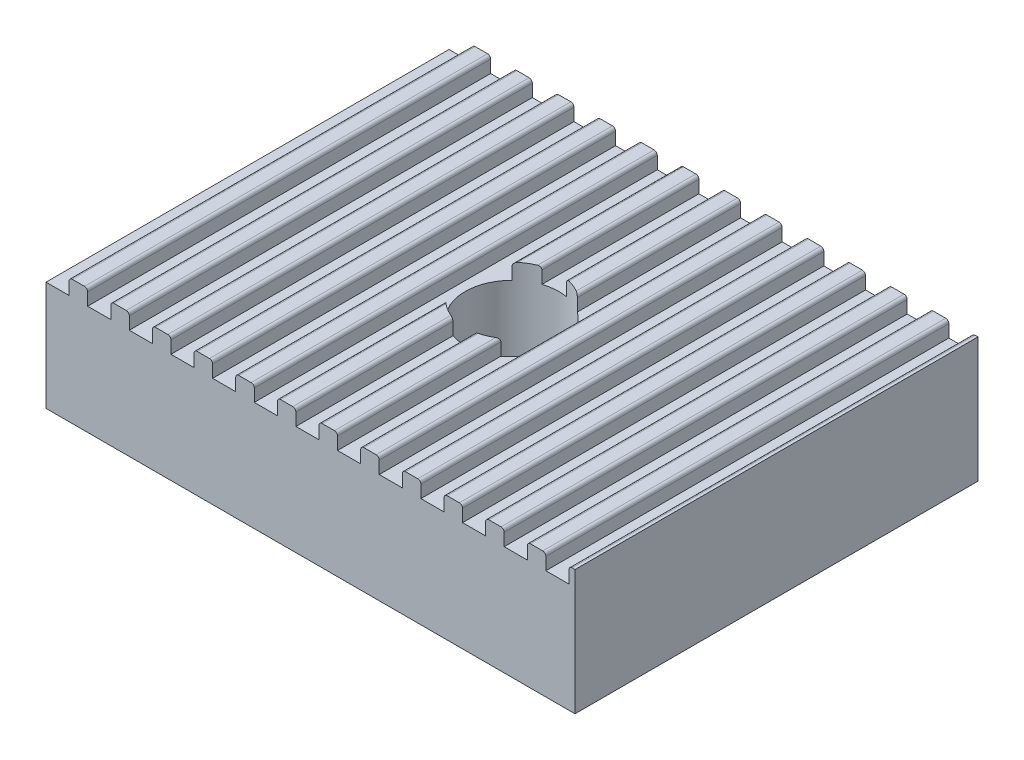
SolidWorks part; units mm, degrees
ref_plane "Front Plane" through (0, 0, 0) normal (0, 0, 1) x (1, 0, 0)
ref_plane "Top Plane" through (0, 0, 0) normal (0, 1, 0) x (1, 0, 0)
ref_plane "Right Plane" through (0, 0, 0) normal (1, 0, 0) x (0, 0, -1)
sketch "Sketch1" plane through (0, 0, 0) normal (0, 1, 0) x (1, 0, 0)
  line L1 (-12.7, -9.675) -> (12.7, -9.675)
  line L2 (-12.7, -9.675) -> (-12.7, 9.675)
  line L3 (-12.7, 9.675) -> (12.7, 9.675)
  line L4 (12.7, -9.675) -> (12.7, 9.675)
  line L5 (-12.7, -9.675) -> (12.7, 9.675) construction
  line L6 (-12.7, 9.675) -> (12.7, -9.675) construction
  point P0 (0, 0)
  dimension "D1" = 25.4
  dimension "D2" = 19.35
extrude "Boss-Extrude1" add sketch "Sketch1" along normal blind 6
sketch "Sketch2" plane through (0, 0, 9.675) normal (0, 0, 1) x (1, 0, 0)
  line L0 (-12.7, 5.25) -> (-11.59, 5.25)
  line L1 (-12.7, 6) -> (-12.7, 0) construction
  line L2 (-11.59, 5.25) -> (-11.59, 6)
  line L3 (-12.7, 6) -> (12.7, 6) construction
  line L4 (-11.59, 6) -> (-10.7, 6)
  line L5 (-9.59, 6) -> (-9.59, 5.25)
  line L6 (-9.59, 5.25) -> (-10.7, 5.25)
  line L7 (-10.7, 5.25) -> (-10.7, 6)
  line L8 (-12.7, 5.25) -> (-12.7, 6)
  line L9 (-9.59, 6) -> (-10.7, 6)
  line L10 (-11.59, 6) -> (-12.7, 6)
  line M3 (12.7, 6) -> (-12.7, 6)
  line M4 (-12.7, 6) -> (-12.7, 0)
  dimension "D1" = 0.75
  dimension "D2" = 1.11
  dimension "D3" = 0.89
extrude "Cut-Extrude3" cut sketch "Sketch2" against normal through all contours L0 L2 M3 M4
pattern_linear "LPattern2" count 13 spacing 2 along (1, 0, 0) of "Cut-Extrude3"
fillet "Fillet1" radius 0.15 25 edges at (-10.7, 6, 0) (-11.59, 6, 0) (12.41, 6, 0) (10.41, 6, 0) (11.3, 6, 0) (8.41, 6, 0) (9.3, 6, 0) (6.41, 6, 0) (7.3, 6, 0) (4.41, 6, 0) (5.3, 6, 0) (2.41, 6, 0) (3.3, 6, 0) (0.41, 6, 0) (1.3, 6, 0) (-1.59, 6, 0) (-0.7, 6, 0) (-3.59, 6, 0) (-2.7, 6, 0) (-5.59, 6, 0) (-4.7, 6, 0) (-7.59, 6, 0) (-6.7, 6, 0) (-9.59, 6, 0) (-8.7, 6, 0)
sketch "Sketch3" plane through (0, 0, 0) normal (0, -1, 0) x (1, 0, 0)
  point P0 (0, 0)
hole_wizard "M4 Clearance Hole1" positions "Sketch4" profile "Sketch5" hole size "M4" standard "ANSI Metric" end condition through all
sketch "Sketch4" plane through (0, 0, 0) normal (0, -1, 0) x (-1, 0, 0)
  point P0 (0, 0)
sketch "Sketch5" plane through (0, 0, 0) normal (1, 0, 0) x (0, 0, -1)
  line L0 (0, 0) -> (0, 6)
  line L1 (0, 6) -> (2.25, 6)
  line L2 (2.25, 6) -> (2.25, 0)
  line L5 (2.25, 0) -> (0, 0)
  line L11 (0, -6.35) -> (0, 107.95) construction
  dimension "Thru Hole Dia." = 4.5
  dimension "Thru Hole Depth" = 6
